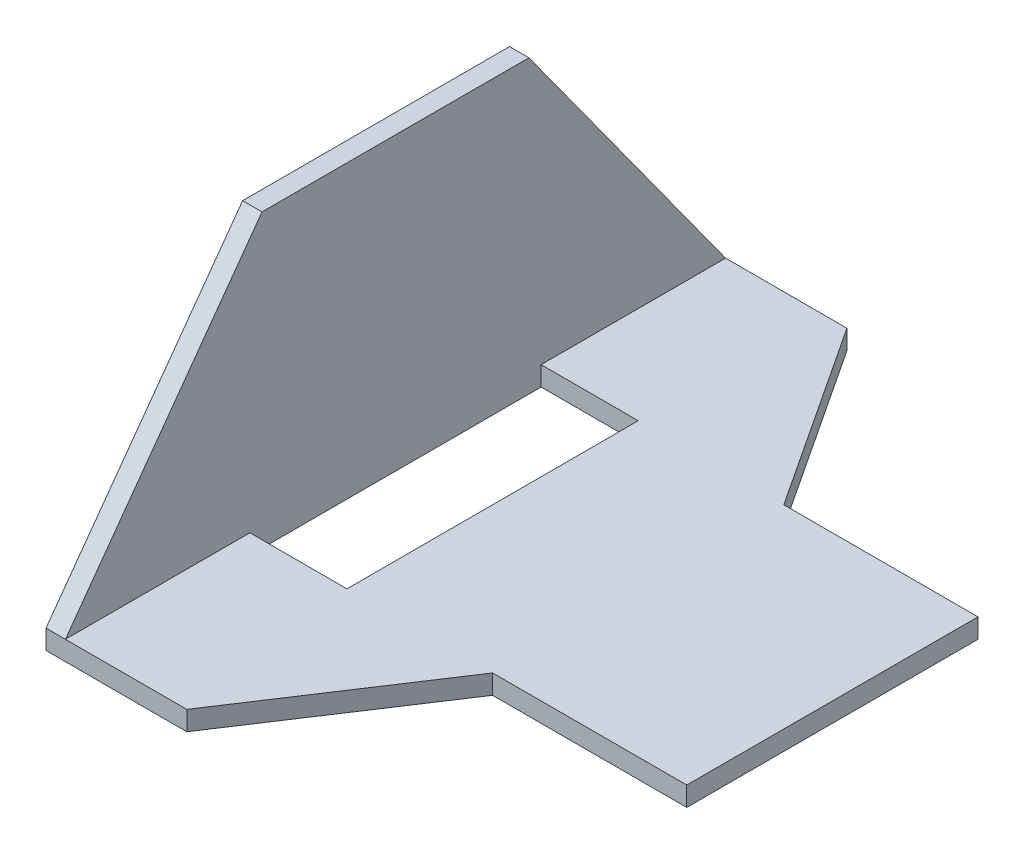
SolidWorks part; units mm, degrees
ref_plane "Front Plane" through (0, 0, 0) normal (0, 0, 1) x (1, 0, 0)
ref_plane "Top Plane" through (0, 0, 0) normal (0, 1, 0) x (1, 0, 0)
ref_plane "Right Plane" through (0, 0, 0) normal (1, 0, 0) x (0, 0, -1)
sketch "Sketch1" plane through (0, 0, 0) normal (0, 1, 0) x (1, 0, 0)
  line L0 (-55, 0) -> (55, 0) construction
  line L1 (-15, 30) -> (25, 30)
  line L2 (25, 30) -> (25, -30)
  line L3 (-45, 30) -> (-45, -30)
  line L4 (0, -55) -> (0, 55) construction
  line L6 (-15, 30) -> (-40, 68)
  line L7 (-40, 68) -> (-65, 68)
  line L8 (-65, 68) -> (-65, 30)
  line L9 (-67.3833, 0) -> (70.6871, 0) construction
  line L10 (-45, -30) -> (-65, -30)
  line L11 (-65, -68) -> (-65, -30)
  line L12 (-40, -68) -> (-65, -68)
  line L13 (-15, -30) -> (-40, -68)
  line L14 (-45, 30) -> (-65, 30)
  line L15 (-15, -30) -> (25, -30)
  point P19 (-45, 0)
  point P21 (25, 0)
  dimension "D1" = 30
  dimension "D2" = 30
  dimension "D3" = 38
  dimension "D4" = 70
  dimension "D5" = 40
  dimension "D6" = 25
  dimension "D7" = 40
  dimension "D8" = 25
extrude "Boss-Extrude1" add sketch "Sketch1" along normal blind 4
sketch "Sketch3" plane through (-65, 0, 0) normal (-1, 0, 0) x (0, 0, 1)
  line L0 (-68, 0) -> (-68, 4)
  line L1 (49.5, 0) -> (-49.5, 0) construction
  line L2 (-68, 4) -> (-27.5, 60)
  line L3 (-27.5, 60) -> (27.5, 60)
  line L4 (27.5, 60) -> (68, 4)
  line L5 (68, 4) -> (68, 0) construction
  line L6 (68, 4) -> (68, 0)
  line L7 (68, 0) -> (-68, 0)
  line L8 (0, -2.2) -> (0, 2.2) construction
  dimension "D1" = 55
  dimension "D2" = 60
  dimension "D3" = 27.5
  dimension "D4" = 4
  dimension "D5" = 136
extrude "Boss-Extrude3" add sketch "Sketch3" along normal blind 4
